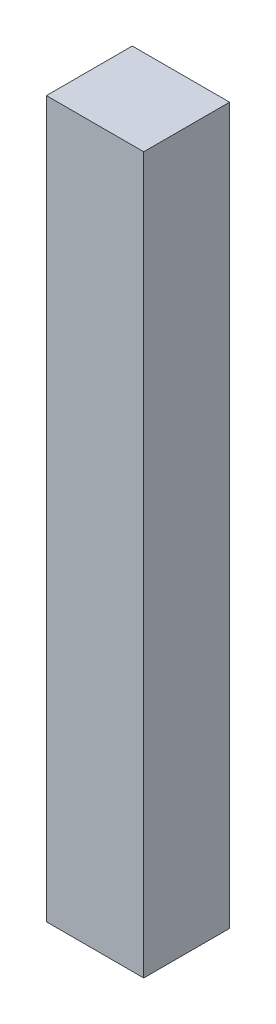
SolidWorks part; units mm, degrees
ref_plane "Front Plane" through (0, 0, 0) normal (0, 0, 1) x (1, 0, 0)
ref_plane "Top Plane" through (0, 0, 0) normal (0, 1, 0) x (1, 0, 0)
ref_plane "Right Plane" through (0, 0, 0) normal (1, 0, 0) x (0, 0, -1)
sketch "Sketch1" plane through (0, 0, 0) normal (0, 0, 1) x (1, 0, 0)
  line L1 (-1.7, 12.5) -> (1.7, 12.5)
  line L2 (-1.7, 12.5) -> (-1.7, -12.5)
  line L3 (-1.7, -12.5) -> (1.7, -12.5)
  line L4 (1.7, 12.5) -> (1.7, -12.5)
  line L5 (-1.7, 12.5) -> (1.7, -12.5) construction
  line L6 (-1.7, -12.5) -> (1.7, 12.5) construction
  point P0 (0, 0)
  dimension "D1" = 25
  dimension "D2" = 3.4
extrude "Boss-Extrude1" add sketch "Sketch1" along normal blind 3
